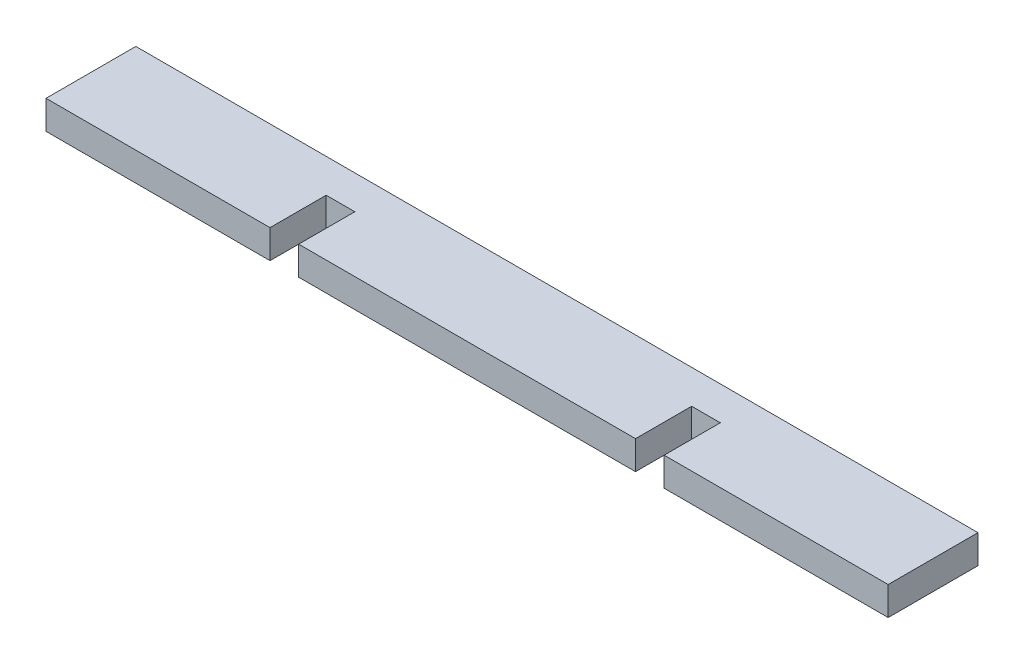
SolidWorks part; units mm, degrees
ref_plane "Front Plane" through (0, 0, 0) normal (0, 0, 1) x (1, 0, 0)
ref_plane "Top Plane" through (0, 0, 0) normal (0, 1, 0) x (1, 0, 0)
ref_plane "Right Plane" through (0, 0, 0) normal (1, 0, 0) x (0, 0, -1)
sketch "Sketch1" plane through (0, 0, 0) normal (0, 1, 0) x (1, 0, 0)
  line L0 (-35.1, -8) -> (-35.1, 2)
  line L1 (75, -8) -> (35.1, -8)
  line L2 (75, -8) -> (75, 8)
  line L3 (75, 8) -> (-75, 8)
  line L4 (-75, -8) -> (-75, 8)
  line L5 (75, -8) -> (-75, 8) construction
  line L6 (75, 8) -> (-75, -8) construction
  line L7 (-35.1, 2) -> (-30, 2)
  line L8 (-30, 2) -> (-30, -8)
  line L9 (30, -8) -> (30, 2)
  line L10 (30, 2) -> (35.1, 2)
  line L11 (35.1, 2) -> (35.1, -8)
  line L12 (-35.1, -8) -> (-75, -8)
  line L13 (30, -8) -> (-30, -8)
  point P0 (0, 0)
  dimension "D1" = 150
  dimension "D2" = 16
  dimension "D3" = 5.1
  dimension "D4" = 5.1
  dimension "D5" = 10
  dimension "D6" = 10
  dimension "D7" = 60
  dimension "D8" = 30
extrude "Boss-Extrude1" add sketch "Sketch1" along normal blind 5.1
